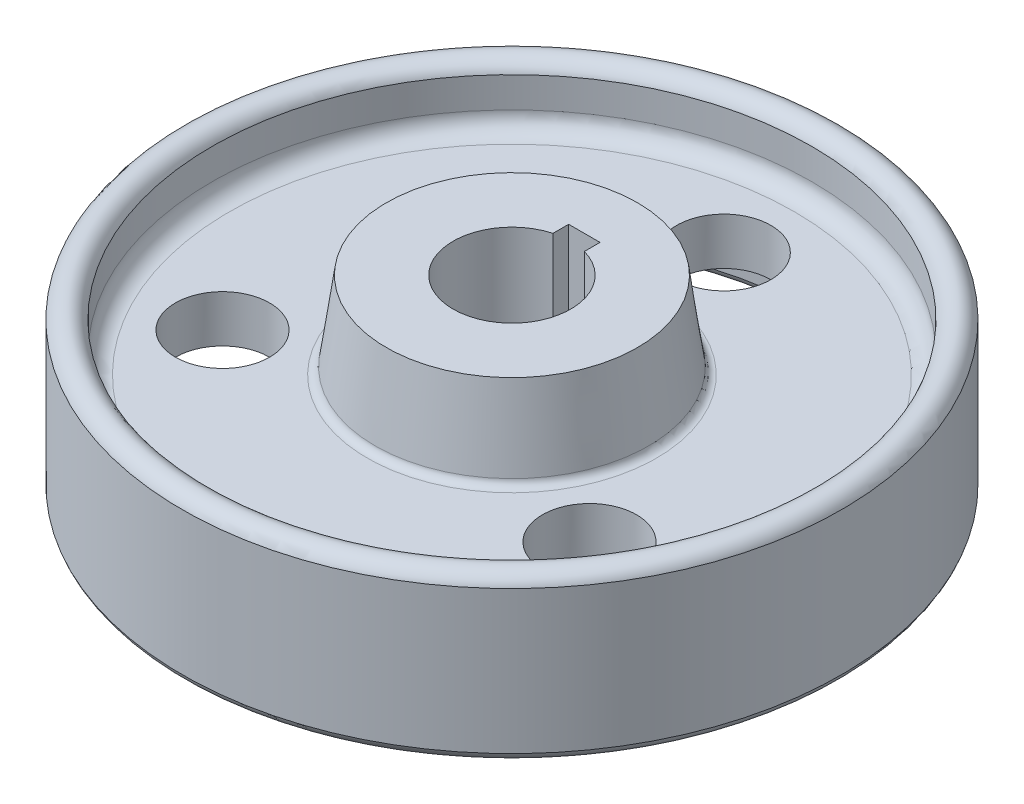
SolidWorks part; units mm, degrees
ref_plane "Plan de face" through (0, 0, 0) normal (0, 0, 1) x (1, 0, 0)
ref_plane "Plan de dessus" through (0, 0, 0) normal (0, 1, 0) x (1, 0, 0)
ref_plane "Plan de droite" through (0, 0, 0) normal (1, 0, 0) x (0, 0, -1)
sketch "Esquisse6" plane through (0, 0, 0) normal (1, 0, 0) x (0, 0, -1)
  line L0 (0, 0) -> (0, 63.4067) construction
  line L1 (0, 0) -> (11.9062, 0)
  line L2 (11.9062, -22.225) -> (11.9062, 22.225)
  line L3 (11.9062, 22.225) -> (25.4, 22.225)
  line L4 (25.4, 22.225) -> (27.6621, 6.1291)
  line L5 (29.2342, 4.7625) -> (57.15, 4.7625)
  line L10 (66.675, 0) -> (0, 0)
  line L11 (63.6699, 17.4625) -> (63.6699, 13.4326) construction
  line L12 (66.675, -14.4574) -> (66.675, 14.4574)
  line L13 (60.6649, 14.4574) -> (60.6649, 8.2774)
  line L14 (63.6699, -17.4625) -> (63.6699, -13.4326) construction
  line L15 (60.6649, -14.4574) -> (60.6649, -8.2774)
  line L16 (11.9062, -22.225) -> (25.4, -22.225)
  line L17 (29.2342, -4.7625) -> (57.15, -4.7625)
  line L18 (25.4, -22.225) -> (27.6621, -6.1291)
  arc A0 (29.2342, 4.7625) -> (27.6621, 6.1291) centre (29.2342, 6.35) cw
  arc A1 (66.675, 14.4574) -> (60.6649, 14.4574) centre (63.6699, 13.4326) ccw
  arc A2 (57.15, 4.7625) -> (60.6649, 8.2774) centre (57.15, 8.2774) ccw
  arc A3 (66.675, -14.4574) -> (60.6649, -14.4574) centre (63.6699, -13.4326) cw
  arc A4 (57.15, -4.7625) -> (60.6649, -8.2774) centre (57.15, -8.2774) cw
  arc A5 (29.2342, -4.7625) -> (27.6621, -6.1291) centre (29.2342, -6.35) ccw
  point P14 (27.8542, 4.7625)
  point P17 (60.325, 17.4625)
  point P26 (60.325, -17.4625)
  point P32 (27.8542, -4.7625)
  dimension "D11" = 1.5875
  dimension "D12" = 3.175
  dimension "D1" = 11.9062
  dimension "D2" = 17.4625
  dimension "D3" = 25.4
  dimension "D4" = 82
  dimension "D5" = 9.525
  dimension "D6" = 57.15
  dimension "D8" = 22.225
  dimension "D10" = 66.675
revolve "Tour complet" add sketch "Esquisse6" angle 360 about L0
sketch "Esquisse7" plane through (0, 22.225, 0) normal (0, 1, 0) x (1, 0, 0)
  line L1 (-3.175, 14.6501) -> (3.175, 14.6501)
  line L2 (-3.175, 14.6501) -> (-3.175, 11.4751)
  line L4 (3.175, 14.6501) -> (3.175, 11.4751)
  circle A0 centre (0, 0) radius 11.9062 construction
  circle A2 centre (0, 0) radius 11.9062
  arc A3 (3.175, 11.4751) -> (-3.175, 11.4751) centre (0, 0) ccw
  dimension "D1" = 6.35
  dimension "D2" = 3.175
  dimension "D3" = 0
extrude "Channel" cut sketch "Esquisse7" against normal blind 127
sketch "Esquisse8" plane through (0, 4.7625, 0) normal (0, 1, 0) x (1, 0, 0)
  circle A3 centre (0, 42.8625) radius 9.525
  circle A4 centre (-37.12, -21.4313) radius 9.525
  circle A5 centre (37.12, -21.4313) radius 9.525
  dimension "D4" = 19.05
extrude "Enlèv. mat.-Extru.4" cut sketch "Esquisse8" against normal blind 127
